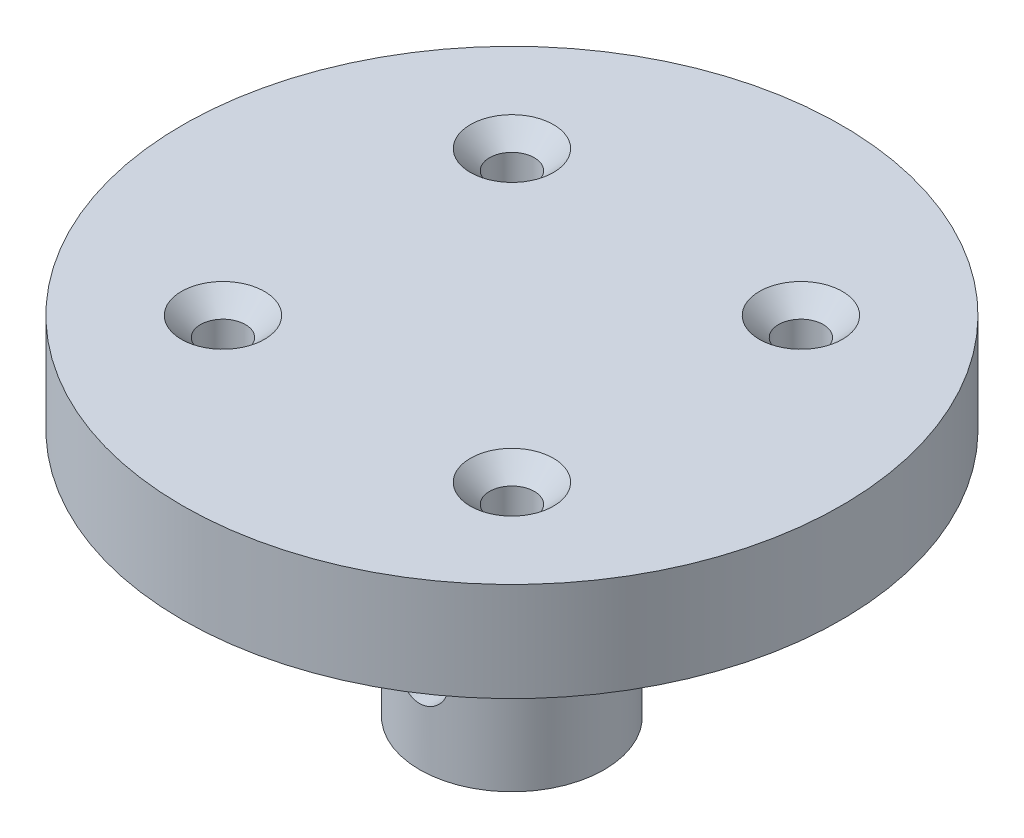
SolidWorks part; units mm, degrees
ref_plane "Front Plane" through (0, 0, 0) normal (0, 0, 1) x (1, 0, 0)
ref_plane "Top Plane" through (0, 0, 0) normal (0, 1, 0) x (1, 0, 0)
ref_plane "Right Plane" through (0, 0, 0) normal (1, 0, 0) x (0, 0, -1)
sketch "Sketch1" plane through (0, 0, 0) normal (0, 1, 0) x (1, 0, 0)
  line L1 (-25, -25) -> (25, -25)
  line L2 (-25, -25) -> (-25, 25)
  line L3 (-25, 25) -> (25, 25)
  line L4 (25, -25) -> (25, 25)
  line L5 (-25, -25) -> (25, 25) construction
  line L6 (-25, 25) -> (25, -25) construction
  circle A0 centre (0, 0) radius 25
  circle A1 centre (0, 0) radius 5
  dimension "D1" = 50
  dimension "D2" = 10
extrude "Boss-Extrude1" add sketch "Sketch1" along normal blind 7.5 contours A0 A1
sketch "Sketch2" plane through (0, 7.5, 0) normal (0, 1, 0) x (1, 0, 0)
  line L1 (-25, -25) -> (25, -25)
  line L2 (-25, -25) -> (-25, 25)
  line L3 (-25, 25) -> (25, 25)
  line L4 (25, -25) -> (25, 25)
  line L5 (-25, -25) -> (25, 25) construction
  line L6 (-25, 25) -> (25, -25) construction
  line L7 (-8.3085, 13.6118) -> (-13.6118, 8.3085) construction
  circle A0 centre (0, 0) radius 25 construction
  point P0 (0, 0)
  point P15 (-10.9602, 10.9602)
  point P18 (10.9602, 10.9602)
  point P19 (10.9602, -10.9602)
  point P20 (-10.9602, -10.9602)
  dimension "D2" = 15.5
  dimension "D3" = 7.5
  dimension "D5" = 15.5
  dimension "D4" = 4
hole_wizard "CSK for M3 Flat Head Machine Screw1" positions "3DSketch2" profile "Sketch5" countersink size "M3" standard "ANSI Metric" end condition through all
sketch3d "3DSketch2"
  point P0 (-10.9602, 7.5, -10.9602)
  point P3 (10.9602, 7.5, -10.9602)
  point P6 (10.9602, 7.5, 10.9602)
  point P9 (-10.9602, 7.5, 10.9602)
sketch "Sketch5" plane through (-10.9602, 7.5, -10.9602) normal (1, 0, 0) x (0, 0, 1)
  line L0 (0, 0) -> (0, 7.5)
  line L1 (0, 7.5) -> (1.725, 7.5)
  line L2 (1.7, 7.475) -> (1.7, 1.45)
  line L3 (1.7, 1.45) -> (3.15, 0)
  line L5 (3.15, 0) -> (0, 0)
  line L6 (-1.7, 1.45) -> (-3.15, 0) construction
  line L7 (1.725, 7.5) -> (1.7, 7.475)
  line L8 (-1.725, 7.5) -> (-1.7, 7.475) construction
  line L11 (0, -6.35) -> (0, 107.95) construction
  dimension "Thru Hole Dia." = 3.4
  dimension "Thru Hole Depth" = 7.5
  dimension "Near C'Sink Dia." = 6.3
  dimension "Near C'Sink Angle" = 90
  dimension "Far C'Sink Dia." = 3.45
  dimension "Far C'Sink Angle" = 90
sketch "Sketch6" plane through (0, 0, 0) normal (0, -1, 0) x (1, 0, 0)
  line L0 (2.6458, 3) -> (-2.6458, 3)
  circle A1 centre (0, 0) radius 4
  circle A3 centre (0, 0) radius 7
  dimension "D2" = 8
  dimension "D1" = 3
  dimension "D3" = 3
extrude "Boss-Extrude2" add sketch "Sketch6" along normal blind 18.85
ref_plane "Plane1" through (0, 0, 7) normal (0, 0, 1) x (1, 0, 0)
sketch "Sketch7" plane through (0, 0, 0) normal (0, 0, 1) x (1, 0, 0)
  line L0 (0, -6.35) -> (0, -18.85)
  line L1 (-7, 0) -> (-7, -18.85) construction
  line L2 (-7, -12.6) -> (7, -12.6)
  line L4 (0, 0) -> (0, -6.35)
  line L5 (-7, -18.85) -> (7, -18.85) construction
  circle A0 centre (0, -12.6) radius 1
  circle A1 centre (0, -12.6) radius 1.9
  point P0 (0, -18.8481)
  point P2 (0, 0)
  point P3 (0, 12.7)
  point P8 (0, -10.9925)
  point P9 (-0.1256, -15.5749)
  point P10 (0, -12.6)
  point P13 (-0.1672, -13.3399)
  point P14 (-0.1103, -9.425)
  point P15 (0, 0)
  point P16 (0.1638, -6.35)
  dimension "D1" = 2
  dimension "D2" = 3.8
  dimension "D3" = 12.6
extrude "Cut-Extrude1" cut sketch "Sketch7" along normal blind 10.5 contours A0
sketch "Sketch11" plane through (0, 0, 7) normal (0, 0, 1) x (1, 0, 0)
  line L0 (0, 0) -> (0, -6.35)
  circle A0 centre (0, -12.6) radius 1.9
  point P3 (0, -12.6)
  point P4 (0, -9.425)
  point P6 (0, 0)
  point P14 (0, 0)
  dimension "D1" = 3.8
  dimension "D2" = 6.35
extrude "Cut-Extrude2" cut sketch "Sketch11" against normal blind 2 contours A0
